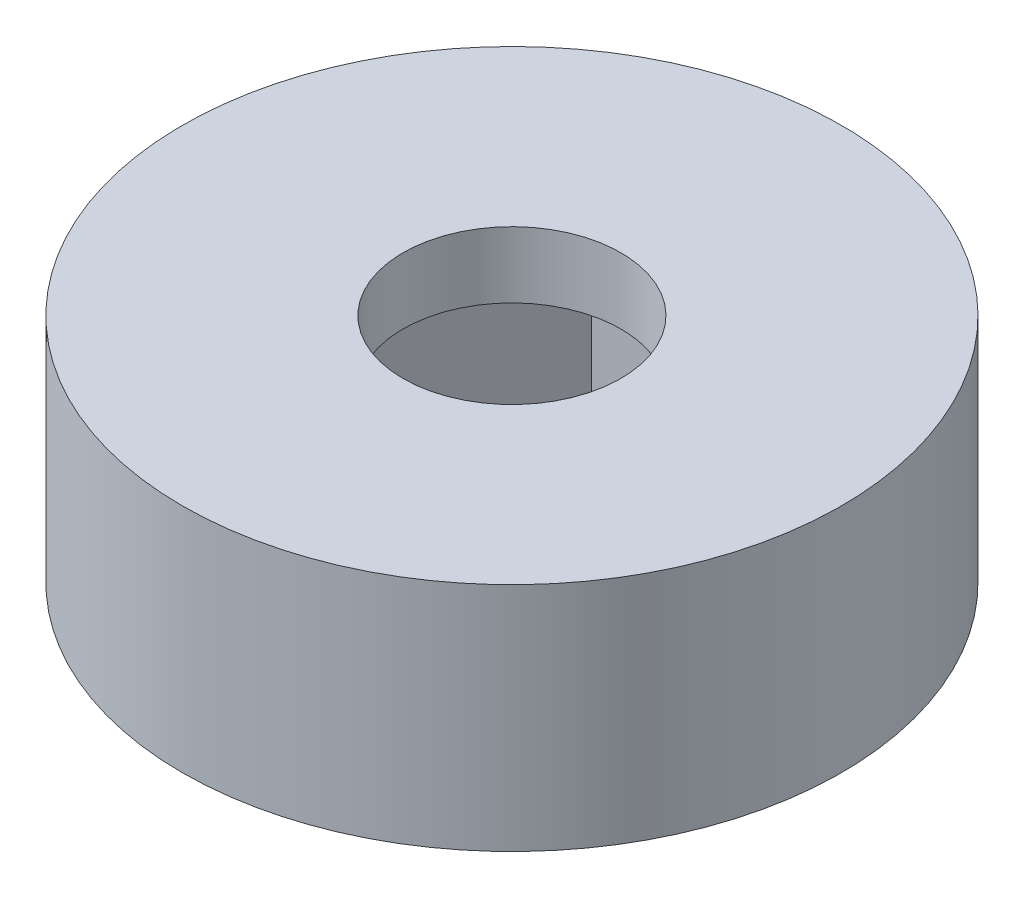
SolidWorks part; units mm, degrees
ref_plane "前视基准面" through (0, 0, 0) normal (0, 0, 1) x (1, 0, 0)
ref_plane "上视基准面" through (0, 0, 0) normal (0, 1, 0) x (1, 0, 0)
ref_plane "右视基准面" through (0, 0, 0) normal (1, 0, 0) x (0, 0, -1)
sketch "草图1" plane through (0, 0, 0) normal (0, 1, 0) x (1, 0, 0)
  line L1 (1.6454, -2.85) -> (3.2909, 0)
  line L2 (3.2909, 0) -> (1.6454, 2.85)
  line L3 (1.6454, 2.85) -> (-1.6454, 2.85)
  line L4 (-1.6454, 2.85) -> (-3.2909, 0)
  line L5 (-3.2909, 0) -> (-1.6454, -2.85)
  line L6 (-1.6454, -2.85) -> (1.6454, -2.85)
  circle A0 centre (0, 0) radius 2.85 construction
  circle A1 centre (0, 0) radius 4.9909
  circle A2 centre (0, 0) radius 3.2909 construction
  dimension "D1" = 5.7
  dimension "D2" = 1.7
extrude "凸台-拉伸1" add sketch "草图1" along normal blind 2.5
sketch "草图2" plane through (0, 2.5, 0) normal (0, 1, 0) x (1, 0, 0)
  circle A0 centre (0, 0) radius 4.9909
  circle A1 centre (0, 0) radius 1.65
  dimension "D1" = 3.3
extrude "凸台-拉伸2" add sketch "草图2" along normal blind 1
